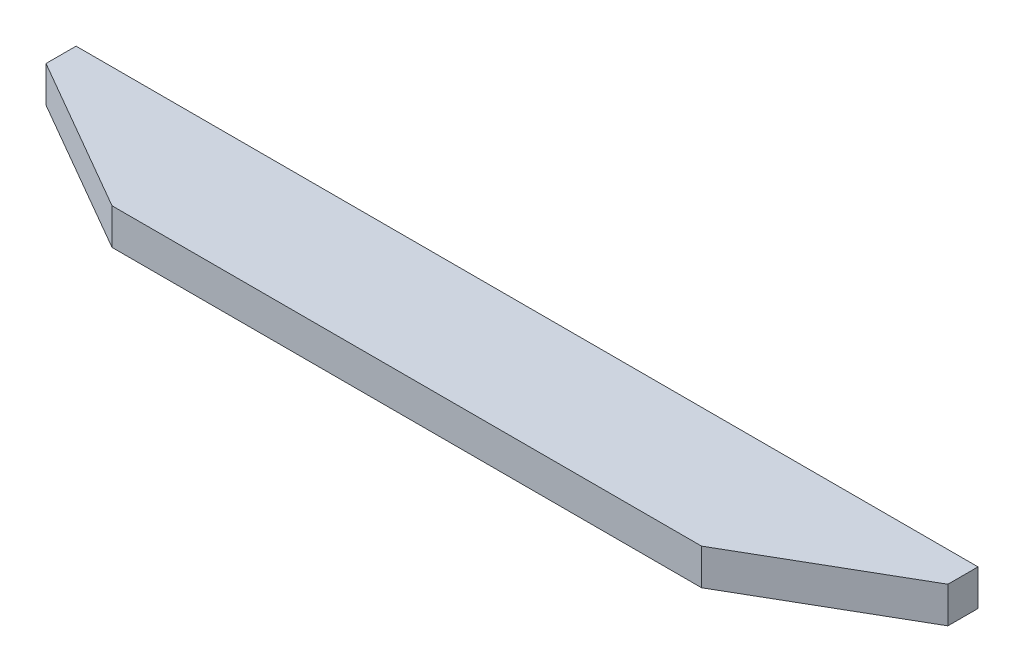
SolidWorks part; units mm, degrees
material "AISI 304"
ref_plane "Спереди" through (0, 0, 0) normal (0, 0, 1) x (1, 0, 0)
ref_plane "Сверху" through (0, 0, 0) normal (0, 1, 0) x (1, 0, 0)
ref_plane "Справа" through (0, 0, 0) normal (1, 0, 0) x (0, 0, -1)
other "Configuration Table"
sketch "Эскиз1" plane through (0, 0, 0) normal (0, 0, 1) x (1, 0, 0)
  line L0 (0, 0) -> (0, 14.8157) construction
  line L1 (-75, 6) -> (75, 6)
  line L2 (-75, 6) -> (-75, 0)
  line L3 (-75, 0) -> (75, 0)
  line L4 (75, 6) -> (75, 0)
  dimension "D1" = 150
  dimension "D2" = 6
extrude "Бобышка-Вытянуть1" add sketch "Эскиз1" along normal blind 20
chamfer "Фаска1" distance 15 angle 60 2 edges at (75, 3, 20) (-75, 3, 20)
